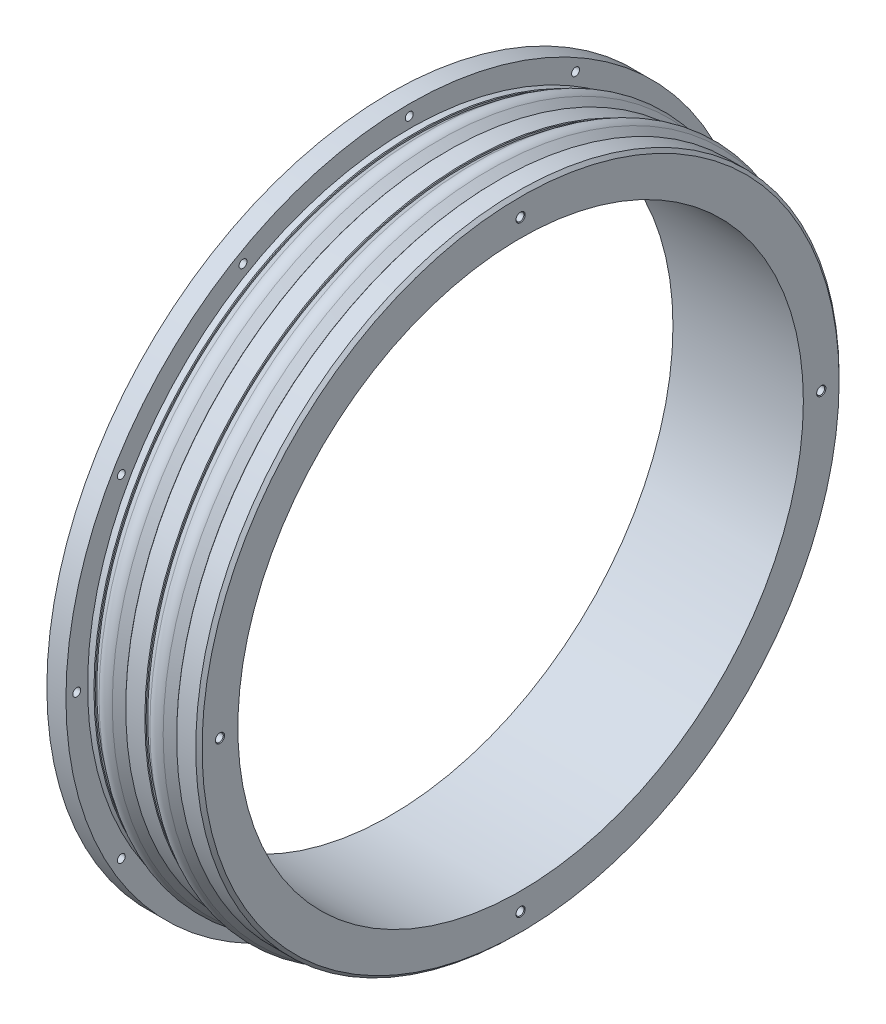
SolidWorks part; units mm, degrees
material "6061 Alloy"
ref_plane "Front Plane" through (0, 0, 0) normal (0, 0, 1) x (1, 0, 0)
ref_plane "Top Plane" through (0, 0, 0) normal (0, 1, 0) x (1, 0, 0)
ref_plane "Right Plane" through (0, 0, 0) normal (1, 0, 0) x (0, 0, -1)
sketch "Sketch2" plane through (0, 0, 0) normal (0, 1, 0) x (1, 0, 0)
  line L0 (0, 0) -> (0, 88.9) construction
  line L1 (0, 88.9) -> (41, 88.9)
  line L2 (41, 88.9) -> (41, 101.15)
  line L3 (41, 101.15) -> (33.8, 101.15)
  line L4 (33.8, 101.15) -> (33.8, 100.15) construction
  line L5 (33.8, 100.15) -> (24.2, 100.15) construction
  line L6 (24.2, 100.15) -> (24.2, 101.15) construction
  line L7 (24.2, 101.15) -> (8.2, 101.15) construction
  line L8 (8.2, 101.15) -> (8.2, 100.15) construction
  line L9 (8.2, 100.15) -> (17.8, 100.15) construction
  line L10 (17.8, 100.15) -> (17.8, 101.15) construction
  line L11 (17.8, 101.15) -> (6, 101.15) construction
  line L12 (6, 101.15) -> (6, 107.95)
  line L13 (6, 107.95) -> (0, 107.95)
  line L14 (0, 107.95) -> (0, 101.27)
  line L15 (0, 101.27) -> (0.75, 101.27)
  line L16 (0.75, 101.27) -> (0.75, 98.171) construction
  line L17 (0.75, 98.171) -> (0, 98.171)
  line L18 (0, 98.171) -> (0, 88.9)
  line L19 (6, 101.4) -> (41, 101.4) construction
  line L20 (6, 101.62) -> (41, 101.62) construction
  line L21 (8.2, 100.45) -> (10.9167, 102.4624)
  line L22 (0, 0) -> (-153832.3837, 0) construction
  line L23 (13, 100.45) -> (13, 100.15) construction
  line L24 (6, 101.15) -> (8.2, 101.15)
  line L25 (17.8, 101.15) -> (24.2, 101.15)
  line L26 (15.0833, 102.4624) -> (17.8, 100.45)
  line L27 (24.2, 100.45) -> (26.9167, 102.4624)
  line L28 (29, 100.45) -> (29, 100.15) construction
  line L29 (31.0833, 102.4624) -> (33.8, 100.45)
  line L30 (0.0113, 100.7289) -> (0.75, 101.27)
  line L31 (0.0113, 98.7121) -> (0.75, 98.171)
  line L32 (8.2, 101.15) -> (8.2, 100.45)
  line L33 (17.8, 100.45) -> (17.8, 101.15)
  line L34 (24.2, 101.15) -> (24.2, 100.45)
  line L35 (33.8, 100.45) -> (33.8, 101.15)
  line L36 (8.2, 100.45) -> (17.8, 100.45) construction
  line L37 (24.2, 100.45) -> (33.8, 100.45) construction
  line L38 (41, 96.15) -> (0, 96.15) construction
  arc A0 (0.0113, 100.7289) -> (0.0113, 98.7121) centre (0.75, 99.7205) ccw
  arc A1 (10.9167, 102.4624) -> (15.0833, 102.4624) centre (13, 99.65) cw
  arc A2 (26.9167, 102.4624) -> (31.0833, 102.4624) centre (29, 99.65) cw
  dimension "D3" = 1.25
  dimension "D8" = 12
  dimension "D9" = 16
  dimension "D18" = 3.5
  dimension "D1" = 202.8
  dimension "D2" = 203.24
  dimension "D4" = 35
  dimension "D5" = 1
  dimension "D6" = 0.25
  dimension "D7" = 202.3
  dimension "D10" = 196.342
  dimension "D11" = 177.8
  dimension "D12" = 215.9
  dimension "D13" = 6
  dimension "D14" = 9.6
  dimension "D15" = 0.75
  dimension "D16" = 3.099
  dimension "D17" = 0.3
  dimension "D19" = 5
revolve "Revolve1" add sketch "Sketch2" angle 360 about L22
chamfer "Chamfer1" distance 1 angle 45 1 edges at (41, 0, -101.15)
chamfer "Chamfer2" distance 0.2 angle 45 6 edges at (0, 0, -98.171) (0, 0, -101.27) (33.8, 0, -101.15) (24.2, 0, -101.15) (17.8, 0, -101.15) (8.2, 0, -101.15)
sketch "Sketch3" plane through (6, 0, 0) normal (1, 0, 0) x (0, 0, -1)
  line L0 (0, 101.15) -> (0, 107.95) construction
  line L1 (0, -101.15) -> (0, -107.95) construction
  circle A1 centre (0, 0) radius 101.15 construction
  circle A2 centre (0, 0) radius 107.95 construction
  point P9 (0, 104.55)
  point P21 (0, 0)
  point P22 (52.275, 90.543)
  point P23 (90.543, 52.275)
  point P24 (104.55, 0)
  point P25 (90.543, -52.275)
  point P26 (52.275, -90.543)
  point P27 (0, -104.55)
  point P28 (-52.275, -90.543)
  point P29 (-90.543, -52.275)
  point P30 (-104.55, 0)
  point P31 (-90.543, 52.275)
  point P32 (-52.275, 90.543)
  point P33 (0, 0)
  dimension "D1" = 12
hole_wizard "Tap Drill for M3x0.5 Tap2" positions "3DSketch2" profile "Sketch6" hole size "M3x0.5" standard "ANSI Metric" end condition through all
sketch3d "3DSketch2"
  point P0 (6, 104.55, 0)
  point P3 (6, 90.543, -52.275)
  point P6 (6, 52.275, -90.543)
  point P9 (6, 0, -104.55)
  point P12 (6, -52.275, -90.543)
  point P15 (6, -90.543, -52.275)
  point P18 (6, -104.55, 0)
  point P21 (6, -90.543, 52.275)
  point P24 (6, -52.275, 90.543)
  point P27 (6, 0, 104.55)
  point P30 (6, 52.275, 90.543)
  point P33 (6, 90.543, 52.275)
sketch "Sketch6" plane through (6, 104.55, 0) normal (0, 1, 0) x (0, 0, -1)
  line L0 (0, 0) -> (0, 6.5)
  line L1 (0, 6.5) -> (1.25, 6.5)
  line L2 (1.25, 6.5) -> (1.25, 0)
  line L5 (1.25, 0) -> (0, 0)
  line L11 (0, -6.35) -> (0, 107.95) construction
  dimension "Thru Hole Dia." = 2.5
  dimension "Thru Hole Depth" = 6.5
sketch "Sketch7" plane through (41, 0, 0) normal (1, 0, 0) x (0, 0, -1)
  line L0 (0, 100.15) -> (0, 88.9) construction
  line L1 (0, -100.15) -> (0, -88.9) construction
  circle A0 centre (0, 0) radius 100.15 construction
  circle A1 centre (0, 0) radius 88.9 construction
  point P7 (0, 94.525)
  point P11 (94.525, 0)
  point P12 (0, -94.525)
  point P13 (-94.525, 0)
  point P14 (0, 0)
  dimension "D1" = 4
hole_wizard "Tap Drill for M3x0.5 Tap3" positions "3DSketch3" profile "Sketch8" hole size "M3x0.5" standard "ANSI Metric"
sketch3d "3DSketch3"
  point P0 (41, 94.525, 0)
  point P3 (41, 0, -94.525)
  point P6 (41, -94.525, 0)
  point P9 (41, 0, 94.525)
sketch "Sketch8" plane through (41, 94.525, 0) normal (0, 1, 0) x (0, 0, -1)
  line L0 (0, 0) -> (0, 4.7511)
  line L1 (0, 4.7511) -> (1.25, 4)
  line L2 (1.25, 4) -> (1.25, 0)
  line L5 (1.25, 0) -> (0, 0)
  line L10 (0, 4.7511) -> (-1.25, 4) construction
  line L11 (0, -6.35) -> (0, 107.95) construction
  dimension "Hole Dia." = 2.5
  dimension "Hole Depth" = 4
  dimension "Drill Angle" = 118
chamfer "Chamfer3" distance 0.2 angle 45 4 edges at (41, 0, 93.275) (41, -94.525, -1.25) (41, 0, -95.775) (41, 94.525, -1.25)
chamfer "Chamfer4" distance 0.2 angle 45 12 edges at (0, -52.275, -89.293) (0, -90.543, -51.025) (0, -104.55, 1.25) (0, -90.543, 53.525) (0, -52.275, 91.793) (0, 0, 105.8) (0, 52.275, 91.793) (0, 90.543, 53.525) (0, 104.55, 1.25) (0, 90.543, -51.025) (0, 52.275, -89.293) (0, 0, -103.3)
